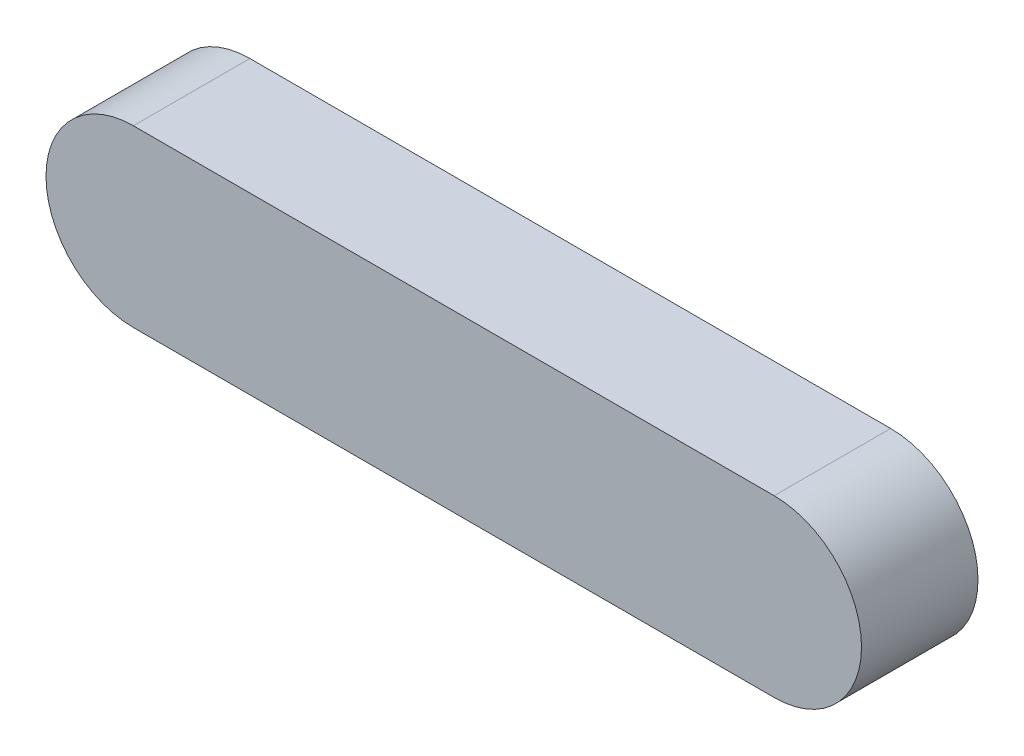
SolidWorks part; units mm, degrees
material "Plain Carbon Steel"
ref_plane "Front Plane" through (0, 0, 0) normal (0, 0, 1) x (1, 0, 0)
ref_plane "Top Plane" through (0, 0, 0) normal (0, 1, 0) x (1, 0, 0)
ref_plane "Right Plane" through (0, 0, 0) normal (1, 0, 0) x (0, 0, -1)
sketch "Sketch1" plane through (0, 0, 0) normal (0, 0, 1) x (1, 0, 0)
  line L0 (-22, 0) -> (22, 0) construction
  line L1 (-22, 6) -> (22, 6)
  line L2 (-22, -6) -> (22, -6)
  arc A0 (-22, 6) -> (-22, -6) centre (-22, 0) ccw
  arc A1 (22, -6) -> (22, 6) centre (22, 0) ccw
  point P2 (0, 0)
  dimension "D2" = 56
  dimension "D1" = 12
extrude "Extrude1" add sketch "Sketch1" along normal blind 8
other "Freeze***"
